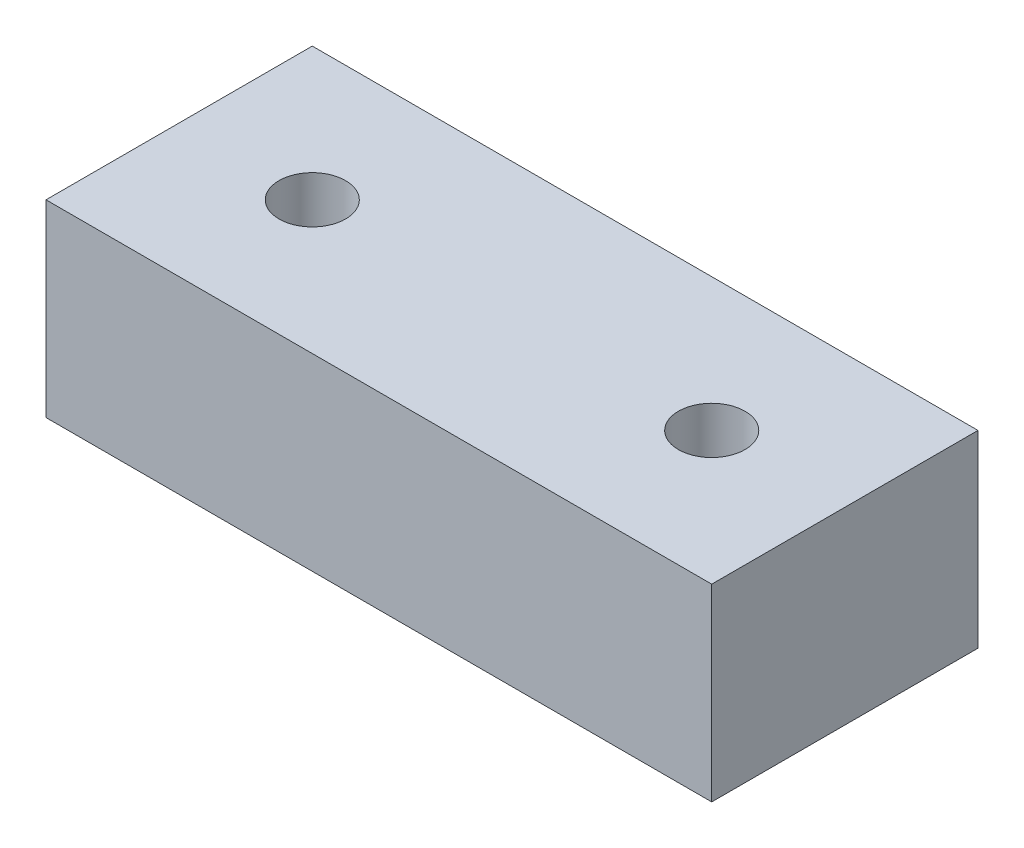
SolidWorks part; units mm, degrees
ref_plane "Front Plane" through (0, 0, 0) normal (0, 0, 1) x (1, 0, 0)
ref_plane "Top Plane" through (0, 0, 0) normal (0, 1, 0) x (1, 0, 0)
ref_plane "Right Plane" through (0, 0, 0) normal (1, 0, 0) x (0, 0, -1)
sketch "Sketch1" plane through (0, 0, 0) normal (0, 1, 0) x (1, 0, 0)
  line L1 (15, 6) -> (-15, 6)
  line L2 (15, 6) -> (15, -6)
  line L3 (15, -6) -> (-15, -6)
  line L4 (-15, 6) -> (-15, -6)
  line L5 (0, -6) -> (0, 6) construction
  line L6 (15, 0) -> (-15, 0) construction
  point P0 (0, 0)
  dimension "D1" = 30
  dimension "D2" = 12
extrude "Boss-Extrude1" add sketch "Sketch1" along normal blind 8.5
sketch "Sketch2" plane through (0, 8.5, 0) normal (0, 1, 0) x (1, 0, 0)
  line L0 (9, 0) -> (-9, 0) construction
  circle A0 centre (-9, 0) radius 1.5
  circle A1 centre (9, 0) radius 1.5
  point P4 (0, 0)
  dimension "D1" = 3
  dimension "D2" = 18
extrude "Cut-Extrude1" cut sketch "Sketch2" against normal through all
